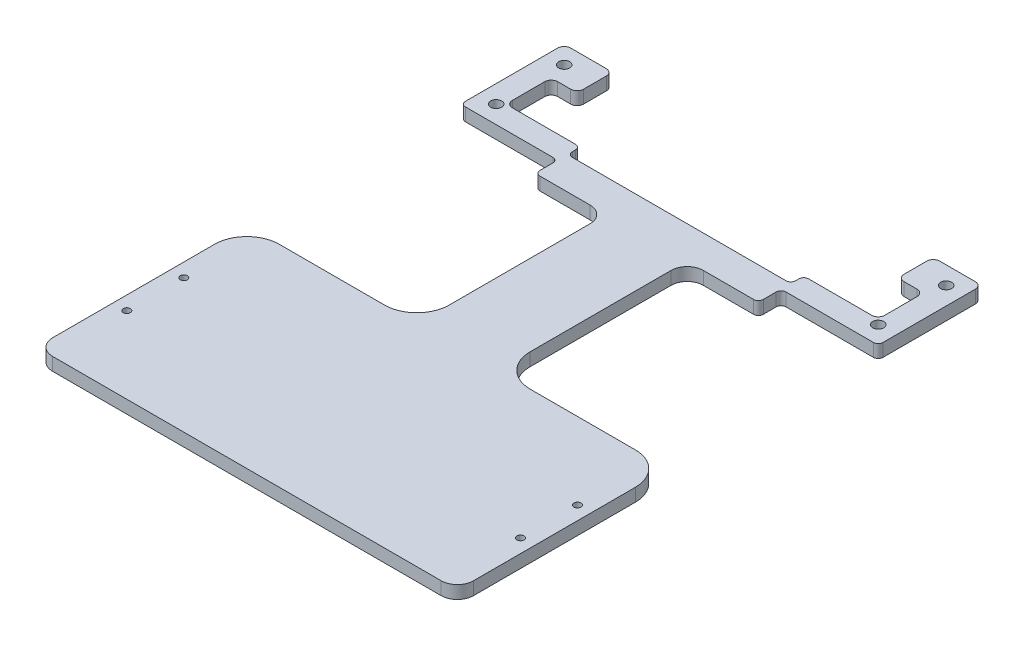
SolidWorks part; units mm, degrees
ref_plane "Front Plane" through (0, 0, 0) normal (0, 0, 1) x (1, 0, 0)
ref_plane "Top Plane" through (0, 0, 0) normal (0, 1, 0) x (1, 0, 0)
ref_plane "Right Plane" through (0, 0, 0) normal (1, 0, 0) x (0, 0, -1)
sketch "Sketch2" plane through (0, 0, 0) normal (0, 1, 0) x (1, 0, 0)
  line L3 (-33, -13) -> (33, -13)
  line L6 (-64.5, 14) -> (-64.5, -13)
  line L7 (64.5, 14) -> (64.5, -13)
  line L8 (-34.5, -10.5) -> (-34.5, -11.5)
  line L10 (-55.5, -9) -> (-36, -9)
  line L11 (-57.5, -7) -> (-57.5, 3)
  line L12 (34.5, -10.5) -> (34.5, -11.5)
  line L13 (-64.5, -13) -> (-64.5, -14.5)
  line L14 (-63, -16) -> (-36, -16)
  line L15 (64.5, -14.5) -> (64.5, -13)
  line L17 (36, -9) -> (55.5, -9)
  line L18 (36, -16) -> (63, -16)
  line L20 (-34.5, -17.5) -> (-34.5, -21.5)
  line L21 (-33, -23) -> (-17.5, -23)
  line L22 (34.5, -17.5) -> (34.5, -21.5)
  line L24 (-62.5, 16) -> (-51.5, 16)
  line L26 (57.5, 3) -> (57.5, -7)
  line L29 (-55.5, 5) -> (-51.5, 5)
  line L30 (-49.5, 14) -> (-49.5, 7)
  line L31 (62.5, 16) -> (51.5, 16)
  line L33 (55.5, 5) -> (51.5, 5)
  line L34 (49.5, 14) -> (49.5, 7)
  line L38 (-12.5, -28) -> (-12.5, -56.5)
  line L40 (12.5, -28) -> (12.5, -56.5)
  line L45 (-55, -81.5) -> (-25, -81.5)
  line L46 (-65, -91.5) -> (-65, -146.5)
  line L47 (-65, -146.5) -> (65, -146.5)
  line L48 (65, -91.5) -> (65, -146.5)
  line L63 (17.5, -23) -> (33, -23)
  line L64 (-25, -81.5) -> (-22.5, -81.5)
  line L65 (-12.5, -71.5) -> (-12.5, -56.5)
  line L67 (12.5, -56.5) -> (12.5, -71.5)
  line L68 (22.5, -81.5) -> (55, -81.5)
  circle A0 centre (59, 10.5) radius 1.7
  circle A1 centre (-59, 10.5) radius 1.7
  circle A2 centre (-59, -10.5) radius 1.7
  circle A3 centre (59, -10.5) radius 1.7
  arc A4 (-55.5, -9) -> (-57.5, -7) centre (-55.5, -7) cw
  arc A5 (55.5, -9) -> (57.5, -7) centre (55.5, -7) ccw
  arc A6 (-34.5, -21.5) -> (-33, -23) centre (-33, -21.5) ccw
  arc A7 (-36, -16) -> (-34.5, -17.5) centre (-36, -17.5) cw
  arc A8 (-34.5, -10.5) -> (-36, -9) centre (-36, -10.5) ccw
  arc A9 (-34.5, -11.5) -> (-33, -13) centre (-33, -11.5) ccw
  arc A10 (33, -23) -> (34.5, -21.5) centre (33, -21.5) ccw
  arc A11 (36, -16) -> (34.5, -17.5) centre (36, -17.5) ccw
  arc A12 (34.5, -10.5) -> (36, -9) centre (36, -10.5) cw
  arc A13 (34.5, -11.5) -> (33, -13) centre (33, -11.5) cw
  arc A14 (64.5, 14) -> (62.5, 16) centre (62.5, 14) ccw
  arc A15 (51.5, 5) -> (49.5, 7) centre (51.5, 7) cw
  arc A16 (51.5, 16) -> (49.5, 14) centre (51.5, 14) ccw
  arc A17 (-62.5, 16) -> (-64.5, 14) centre (-62.5, 14) ccw
  arc A18 (-51.5, 16) -> (-49.5, 14) centre (-51.5, 14) cw
  arc A19 (-51.5, 5) -> (-49.5, 7) centre (-51.5, 7) ccw
  arc A20 (-57.5, 3) -> (-55.5, 5) centre (-55.5, 3) cw
  arc A21 (64.5, -14.5) -> (63, -16) centre (63, -14.5) cw
  arc A22 (-64.5, -14.5) -> (-63, -16) centre (-63, -14.5) ccw
  arc A23 (57.5, 3) -> (55.5, 5) centre (55.5, 3) ccw
  arc A24 (17.5, -23) -> (12.5, -28) centre (17.5, -28) ccw
  arc A25 (-17.5, -23) -> (-12.5, -28) centre (-17.5, -28) cw
  arc A26 (12.5, -71.5) -> (22.5, -81.5) centre (22.5, -71.5) ccw
  arc A27 (-22.5, -81.5) -> (-12.5, -71.5) centre (-22.5, -71.5) ccw
  arc A28 (-55, -81.5) -> (-65, -91.5) centre (-55, -91.5) ccw
  arc A29 (55, -81.5) -> (65, -91.5) centre (55, -91.5) cw
  circle A30 centre (-60.8, -105.2) radius 1.1
  circle A31 centre (-60.8, -122.8) radius 1.1
  circle A32 centre (60.8, -122.8) radius 1.1
  circle A33 centre (60.8, -105.2) radius 1.1
  point P0 (0, 0)
  point P50 (34.5, -16)
  point P53 (34.5, -9)
  point P56 (12.5, -42.25)
  point P71 (49.5, 5)
  point P83 (-49.5, 5)
  point P88 (64.5, -16)
  point P91 (-64.5, -16)
  point P97 (0, -114)
  point P109 (0, -81.5)
  point P113 (49.5, -16)
  point P136 (65, -81.5)
  dimension "D3" = 10
  dimension "D4" = 30
  dimension "D6" = 162.5
  dimension "D9" = 3.4
  dimension "D10" = 3.4
  dimension "D1" = 130
  dimension "D8" = 3.4
  dimension "D12" = 2
  dimension "D13" = 1.5
  dimension "D15" = 2.2
  dimension "D17" = 4.2
  dimension "D18" = 10
  dimension "D19" = 7
  dimension "D11" = 3.4
  dimension "D2" = 65
  dimension "D7" = 25
extrude "Boss-Extrude1" add sketch "Sketch2" along normal blind 4
fillet "Fillet1" radius 5 2 edges at (65, 2, 146.5) (-65, 2, 146.5)
